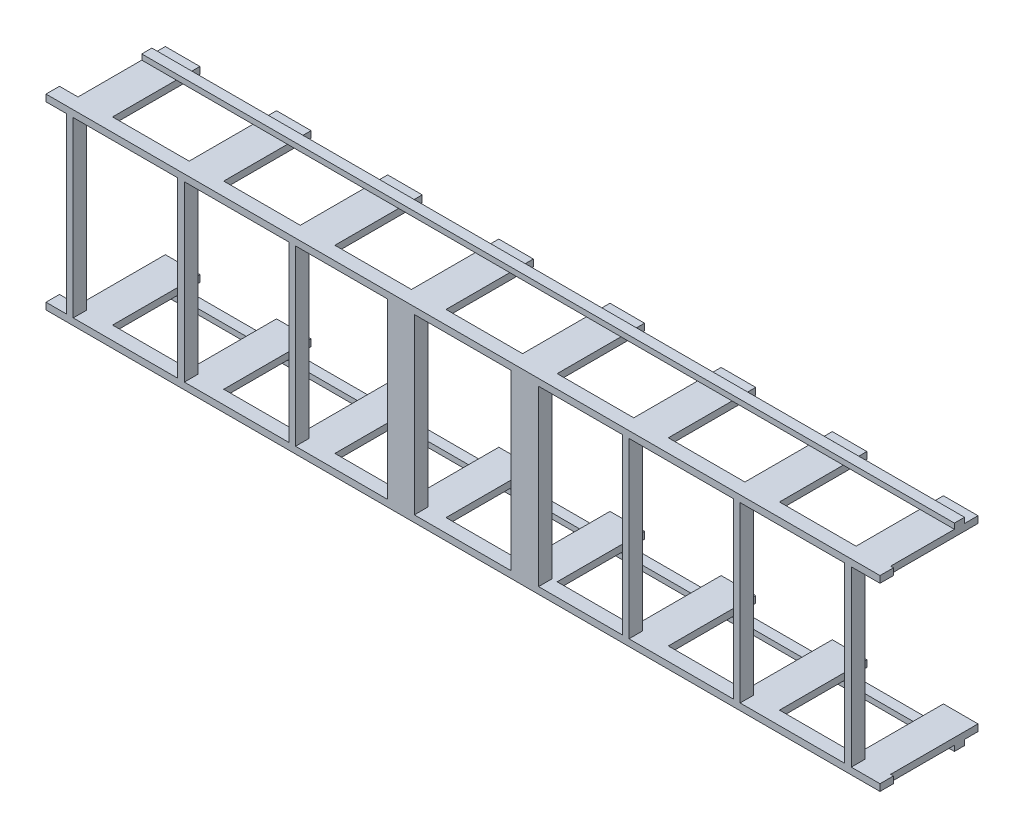
SolidWorks part; units mm, degrees
ref_plane "Front Plane" through (0, 0, 0) normal (0, 0, 1) x (1, 0, 0)
ref_plane "Top Plane" through (0, 0, 0) normal (0, 1, 0) x (1, 0, 0)
ref_plane "Right Plane" through (0, 0, 0) normal (1, 0, 0) x (0, 0, -1)
sketch "Sketch1" plane through (0, 0, 0) normal (0, 0, 1) x (1, 0, 0)
  line L0 (0, 1388) -> (6190, 1388)
  line L1 (0, 50) -> (6190, 50)
  line L2 (0, 50) -> (0, 0)
  line L3 (0, 0) -> (6190, 0)
  line L4 (6190, 50) -> (6190, 0)
  line L5 (0, 1388) -> (0, 1338)
  line L6 (0, 1338) -> (6190, 1338)
  line L7 (6190, 1388) -> (6190, 1338)
  dimension "D1" = 1288
  dimension "D2" = 50
extrude "Boss-Extrude1" add sketch "Sketch1" along normal blind 100
sketch "Sketch2" plane through (0, 0, 0) normal (0, -1, 0) x (1, 0, 0)
  line L0 (0, 100) -> (6190, 100) construction
  line L1 (2534, 100) -> (2734, 100)
  line L2 (2534, 100) -> (2534, 0)
  line L3 (2534, 0) -> (2734, 0)
  line L4 (2734, 100) -> (2734, 0)
  line L5 (0, 0) -> (6190, 0) construction
  line L6 (0, 100) -> (0, 0) construction
  line L8 (3456, 100) -> (3656, 100)
  line L9 (3456, 100) -> (3456, 0)
  line L10 (3456, 0) -> (3656, 0)
  line L11 (3656, 100) -> (3656, 0)
  point P8 (0, 50)
  dimension "D1" = 200
  dimension "D2" = 2534
  dimension "D3" = 2534
  dimension "D4" = 200
extrude "Boss-Extrude2" add sketch "Sketch2" against normal up to surface (1388 mm away) up to face at (3095, 1388, 50)
sketch "Sketch4" plane through (0, 50, 0) normal (0, 1, 0) x (1, 0, 0)
  line L0 (2534, 0) -> (0, 0) construction
  line L1 (152, 0) -> (202, 0)
  line L2 (152, 0) -> (152, -100)
  line L3 (152, -100) -> (202, -100)
  line L4 (202, 0) -> (202, -100)
  line L5 (2534, -100) -> (0, -100) construction
  line L6 (0, -100) -> (0, 0) construction
  line L7 (977, 0) -> (977, -100)
  line L8 (977, 0) -> (1027, 0)
  line L9 (1027, 0) -> (1027, -100)
  line L10 (977, -100) -> (1027, -100)
  line L11 (1802, 0) -> (1802, -100)
  line L12 (1802, 0) -> (1852, 0)
  line L13 (1852, 0) -> (1852, -100)
  line L14 (1802, -100) -> (1852, -100)
  line L15 (2627, 0) -> (2627, -100)
  line L16 (2627, 0) -> (2677, 0)
  line L17 (2677, 0) -> (2677, -100)
  line L18 (2627, -100) -> (2677, -100)
  line L19 (3452, 0) -> (3452, -100)
  line L20 (3452, 0) -> (3502, 0)
  line L21 (3502, 0) -> (3502, -100)
  line L22 (3452, -100) -> (3502, -100)
  line L23 (4277, 0) -> (4277, -100)
  line L24 (4277, 0) -> (4327, 0)
  line L25 (4327, 0) -> (4327, -100)
  line L26 (4277, -100) -> (4327, -100)
  line L27 (5102, 0) -> (5102, -100)
  line L28 (5102, 0) -> (5152, 0)
  line L29 (5152, 0) -> (5152, -100)
  line L30 (5102, -100) -> (5152, -100)
  line L31 (5927, 0) -> (5927, -100)
  line L32 (5927, 0) -> (5977, 0)
  line L33 (5977, 0) -> (5977, -100)
  line L34 (5927, -100) -> (5977, -100)
  dimension "D1" = 152
  dimension "D2" = 50
  dimension "D3" = 8
extrude "Boss-Extrude3" add sketch "Sketch4" along normal up to next (1288 mm away)
sketch "Sketch5" plane through (0, 0, 0) normal (0, 0, 1) x (1, 0, 0)
  line L0 (5912.4, 1388) -> (6169, 1388)
  line L1 (137.4, 1388) -> (137.4, 1338)
  line L2 (394, 50) -> (137.4, 50)
  line L3 (394, 1388) -> (394, 1338)
  line L4 (137.4, 1388) -> (394, 1388)
  line L5 (394, 1338) -> (137.4, 1338)
  line L6 (137.4, 0) -> (394, 0)
  line L7 (394, 0) -> (394, 50)
  line L8 (137.4, 0) -> (137.4, 50)
  line L9 (5912.4, 0) -> (5912.4, 50)
  line L10 (6169, 50) -> (5912.4, 50)
  line L11 (6169, 0) -> (6169, 50)
  line L12 (5087.4, 0) -> (5087.4, 50)
  line L13 (1219, 1388) -> (1219, 1338)
  line L14 (962.4, 1388) -> (1219, 1388)
  line L15 (1219, 1338) -> (962.4, 1338)
  line L16 (5344, 50) -> (5087.4, 50)
  line L17 (962.4, 1388) -> (962.4, 1338)
  line L18 (5087.4, 0) -> (5344, 0)
  line L19 (5344, 0) -> (5344, 50)
  line L20 (4262.4, 0) -> (4262.4, 50)
  line L21 (4519, 50) -> (4262.4, 50)
  line L22 (2044, 1388) -> (2044, 1338)
  line L23 (1787.4, 1388) -> (2044, 1388)
  line L24 (2044, 1338) -> (1787.4, 1338)
  line L25 (4262.4, 0) -> (4519, 0)
  line L26 (1787.4, 1388) -> (1787.4, 1338)
  line L27 (4519, 0) -> (4519, 50)
  line L28 (3437.4, 0) -> (3437.4, 50)
  line L29 (3694, 50) -> (3437.4, 50)
  line L30 (3437.4, 0) -> (3694, 0)
  line L31 (2869, 1388) -> (2869, 1338)
  line L32 (2612.4, 1388) -> (2869, 1388)
  line L33 (2869, 1338) -> (2612.4, 1338)
  line L34 (3694, 0) -> (3694, 50)
  line L35 (2612.4, 1388) -> (2612.4, 1338)
  line L36 (2612.4, 0) -> (2612.4, 50)
  line L37 (2869, 50) -> (2612.4, 50)
  line L38 (2612.4, 0) -> (2869, 0)
  line L39 (2869, 0) -> (2869, 50)
  line L40 (3694, 1388) -> (3694, 1338)
  line L41 (3437.4, 1388) -> (3694, 1388)
  line L42 (3694, 1338) -> (3437.4, 1338)
  line L43 (1787.4, 0) -> (1787.4, 50)
  line L44 (3437.4, 1388) -> (3437.4, 1338)
  line L45 (2044, 50) -> (1787.4, 50)
  line L46 (1787.4, 0) -> (2044, 0)
  line L47 (2044, 0) -> (2044, 50)
  line L48 (962.4, 0) -> (962.4, 50)
  line L49 (4519, 1388) -> (4519, 1338)
  line L50 (4262.4, 1388) -> (4519, 1388)
  line L51 (4519, 1338) -> (4262.4, 1338)
  line L52 (1219, 50) -> (962.4, 50)
  line L53 (4262.4, 1388) -> (4262.4, 1338)
  line L54 (962.4, 0) -> (1219, 0)
  line L55 (1219, 0) -> (1219, 50)
  line L56 (5912.4, 0) -> (6169, 0)
  line L58 (5344, 1388) -> (5344, 1338)
  line L59 (5087.4, 1388) -> (5344, 1388)
  line L60 (5344, 1338) -> (5087.4, 1338)
  line L62 (5087.4, 1388) -> (5087.4, 1338)
  line L67 (6169, 1388) -> (6169, 1338)
  line L69 (6169, 1338) -> (5912.4, 1338)
  line L71 (5912.4, 1388) -> (5912.4, 1338)
  line L73 (152, 694) -> (5977, 694) construction
  line L74 (152, 1338) -> (152, 50) construction
  line L75 (5977, 1338) -> (5977, 50) construction
  line L148 (137.4, 1388) -> (137.4, 1338) [skipped]
  line L149 (140.4, 1385.8) -> (140.4, 1338) [skipped]
  line L150 (140.4, 1338) -> (137.4, 1338) [skipped]
  line L151 (152, 1338) -> (137.4, 1338) construction
  line L152 (137.4, 1388) -> (140.4, 1385.8) [skipped]
  line L153 (965.4, 1385.8) -> (965.4, 1338) [skipped]
  line L154 (962.4, 1388) -> (965.4, 1385.8) [skipped]
  line L155 (965.4, 1338) -> (962.4, 1338) [skipped]
  line L156 (977, 1338) -> (962.4, 1338) construction
  line L157 (1787.4, 1388) -> (1790.4, 1385.8) [skipped]
  line L158 (1790.4, 1385.8) -> (1790.4, 1338) [skipped]
  line L159 (1790.4, 1338) -> (1787.4, 1338) [skipped]
  line L160 (1802, 1338) -> (1787.4, 1338) construction
  line L161 (2612.4, 1388) -> (2615.4, 1385.8) [skipped]
  line L162 (2615.4, 1338) -> (2612.4, 1338) [skipped]
  line L163 (2627, 1338) -> (2612.4, 1338) construction
  line L164 (2615.4, 1385.8) -> (2615.4, 1338) [skipped]
  line L165 (3437.4, 1388) -> (3440.4, 1385.8) [skipped]
  line L166 (3440.4, 1338) -> (3437.4, 1338) [skipped]
  line L167 (3452, 1338) -> (3437.4, 1338) construction
  line L168 (3440.4, 1385.8) -> (3440.4, 1338) [skipped]
  line L169 (4262.4, 1388) -> (4265.4, 1385.8) [skipped]
  line L170 (4265.4, 1338) -> (4262.4, 1338) [skipped]
  line L171 (4277, 1338) -> (4262.4, 1338) construction
  line L172 (4265.4, 1385.8) -> (4265.4, 1338) [skipped]
  line L173 (5087.4, 1388) -> (5090.4, 1385.8) [skipped]
  line L174 (5090.4, 1338) -> (5087.4, 1338) [skipped]
  line L175 (5102, 1338) -> (5087.4, 1338) construction
  line L176 (5090.4, 1385.8) -> (5090.4, 1338) [skipped]
  line L177 (5912.4, 1388) -> (5915.4, 1385.8) [skipped]
  line L178 (5912.4, 1388) -> (6169, 1388) [skipped]
  line L179 (5915.4, 1338) -> (5912.4, 1338) [skipped]
  line L180 (5927, 1338) -> (5912.4, 1338) construction
  line L181 (5915.4, 1385.8) -> (5915.4, 1338) [skipped]
  line L182 (5912.4, 1388) -> (5912.4, 1338) [skipped]
  line L183 (5087.4, 1388) -> (5087.4, 1338) [skipped]
  line L184 (4262.4, 1388) -> (4262.4, 1338) [skipped]
  line L185 (3437.4, 1388) -> (3437.4, 1338) [skipped]
  line L186 (2612.4, 1388) -> (2612.4, 1338) [skipped]
  line L187 (1787.4, 1388) -> (1787.4, 1338) [skipped]
  line L188 (962.4, 1388) -> (962.4, 1338) [skipped]
  line L189 (137.4, 1388) -> (137.4, 1338) [skipped]
  dimension "D2" = 50
  dimension "D3" = 8
extrude "Boss-Extrude4" add sketch "Sketch5" against normal blind 648.4
sketch "Sketch13" plane through (6169, 0, 0) normal (1, 0, 0) x (0, 0, -1)
  line L0 (548.4, 0) -> (473.4, 0)
  line L1 (548.4, 0) -> (548.4, -40)
  line L2 (548.4, -40) -> (473.4, -40)
  line L3 (473.4, 0) -> (473.4, -40)
  line L4 (548.4, 1388) -> (473.4, 1388)
  line L5 (548.4, 1388) -> (548.4, 1428)
  line L6 (548.4, 1428) -> (473.4, 1428)
  line L7 (473.4, 1388) -> (473.4, 1428)
  line L13 (648.4, 0) -> (648.4, 50) construction
  line L14 (648.4, 0) -> (0, 0) construction
  line L15 (648.4, 1388) -> (0, 1388) construction
  dimension "D1" = 75
  dimension "D2" = 40
  dimension "D3" = 40
  dimension "D4" = 75
  dimension "D6" = 100
  dimension "D7" = 0
  dimension "D8" = 0
extrude "Boss-Extrude12" add sketch "Sketch13" against normal up to surface (6031.6 mm away) up to face at (137.4, 1363, -324.2)
